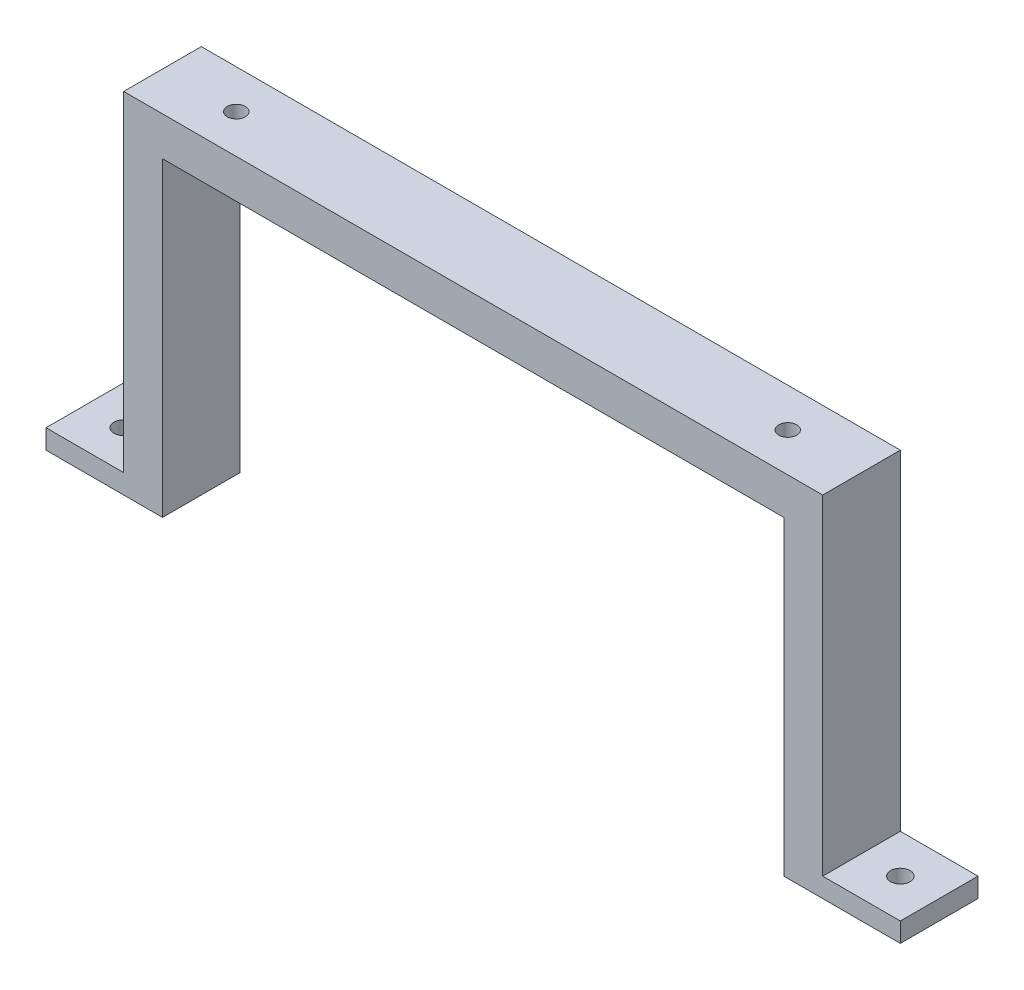
SolidWorks part; units mm, degrees
ref_plane "Front Plane" through (0, 0, 0) normal (0, 0, 1) x (1, 0, 0)
ref_plane "Top Plane" through (0, 0, 0) normal (0, 1, 0) x (1, 0, 0)
ref_plane "Right Plane" through (0, 0, 0) normal (1, 0, 0) x (0, 0, -1)
sketch "Sketch1" plane through (0, 0, 0) normal (0, 1, 0) x (1, 0, 0)
  line L1 (-57.15, 6.35) -> (57.15, 6.35)
  line L2 (-57.15, 6.35) -> (-57.15, -6.35)
  line L3 (-57.15, -6.35) -> (57.15, -6.35)
  line L4 (57.15, 6.35) -> (57.15, -6.35)
  line L5 (-57.15, 6.35) -> (57.15, -6.35) construction
  line L6 (-57.15, -6.35) -> (57.15, 6.35) construction
  point P0 (0, 0)
  dimension "D1" = 12.7
  dimension "D2" = 114.3
extrude "Boss-Extrude1" add sketch "Sketch1" along normal blind 6.35
sketch "Sketch2" plane through (0, 0, 0) normal (0, -1, 0) x (1, 0, 0)
  line L0 (57.15, -6.35) -> (-57.15, -6.35) construction
  line L1 (-57.15, 6.35) -> (-50.8, 6.35)
  line L2 (-57.15, 6.35) -> (-57.15, -6.35)
  line L3 (-57.15, -6.35) -> (-50.8, -6.35)
  line L4 (-50.8, 6.35) -> (-50.8, -6.35)
  dimension "D1" = 6.35
extrude "Boss-Extrude2" add sketch "Sketch2" along normal blind 50.8
sketch "Sketch3" plane through (-57.15, 0, 0) normal (-1, 0, 0) x (0, 0, 1)
  line L0 (6.35, 6.35) -> (6.35, -50.8) construction
  line L1 (-6.35, -50.8) -> (6.35, -50.8)
  line L2 (-6.35, -50.8) -> (-6.35, -47.625)
  line L3 (-6.35, -47.625) -> (6.35, -47.625)
  line L4 (6.35, -50.8) -> (6.35, -47.625)
  dimension "D1" = 3.175
extrude "Boss-Extrude3" add sketch "Sketch3" along normal blind 12.7
mirror "Mirror1" about plane through (0, 0, 0) normal (1, 0, 0) of "Boss-Extrude3", "Boss-Extrude2"
sketch "Sketch4" plane through (0, -47.625, 0) normal (0, 1, 0) x (1, 0, 0)
  line L0 (-69.85, 6.35) -> (-57.15, 6.35) construction
  line L1 (-69.85, -6.35) -> (-69.85, 6.35) construction
  circle A0 centre (-63.5, 0) radius 1.5875
  dimension "D1" = 3.175
  dimension "D3" = 6.35
  dimension "D2" = 6.35
extrude "Cut-Extrude1" cut sketch "Sketch4" against normal up to next
mirror "Mirror2" about plane through (0, 0, 0) normal (1, 0, 0) of "Cut-Extrude1"
sketch "Sketch5" plane through (0, 6.35, 0) normal (0, 1, 0) x (1, 0, 0)
  line L0 (-57.15, -6.35) -> (-57.15, 6.35) construction
  line L1 (57.15, 6.35) -> (-57.15, 6.35) construction
  line L2 (-45.085, 0) -> (45.085, 0) construction
  circle A0 centre (-45.085, 0) radius 1.4732
  circle A1 centre (45.085, 0) radius 1.4732
  dimension "D1" = 2.9464
  dimension "D2" = 2.9464
  dimension "D3" = 90.17
  dimension "D4" = 12.065
  dimension "D5" = 6.35
extrude "Cut-Extrude2" cut sketch "Sketch5" against normal up to next
